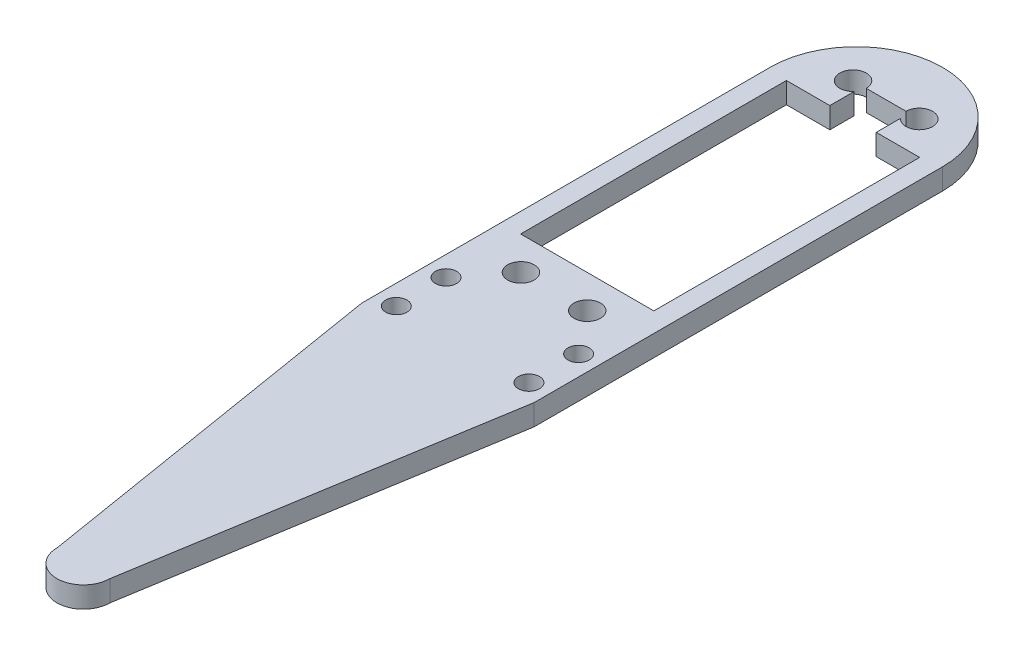
SolidWorks part; units mm, degrees
ref_plane "Front Plane" through (0, 0, 0) normal (0, 0, 1) x (1, 0, 0)
ref_plane "Top Plane" through (0, 0, 0) normal (0, 1, 0) x (1, 0, 0)
ref_plane "Right Plane" through (0, 0, 0) normal (1, 0, 0) x (0, 0, -1)
sketch "Sketch2" plane through (0, 0, 0) normal (0, 1, 0) x (1, 0, 0)
  line L0 (-13, 0) -> (-13, -61.6)
  line L1 (13, 0) -> (13, -61.6)
  line L2 (-13, -61.6) -> (-4, -116.6)
  line L3 (13, -61.6) -> (4, -116.6)
  line L4 (0, 13) -> (0, -120.6) construction
  line L5 (-4, -116.6) -> (4, -116.6) construction
  line L6 (-10.05, -0.5) -> (10.05, -0.5)
  line L7 (-10.05, -0.5) -> (-10.05, -40.6)
  line L8 (-10.05, -40.6) -> (10.05, -40.6)
  line L9 (10.05, -0.5) -> (10.05, -40.6)
  line L10 (-10.05, -0.5) -> (10.05, -40.6) construction
  line L11 (-10.05, -40.6) -> (10.05, -0.5) construction
  arc A0 (13, 0) -> (-13, 0) centre (0, 0) ccw
  arc A1 (-4, -116.6) -> (4, -116.6) centre (0, -116.6) ccw
  circle A2 centre (-5, 4.5) radius 2
  circle A4 centre (-5, -45.6) radius 2
  circle A5 centre (5, -45.6) radius 2
  circle A6 centre (5, 4.5) radius 2
  point P15 (0, -20.55)
  dimension "D1" = 4
  dimension "D8" = 13
  dimension "D10" = 4
  dimension "D2" = 50.1
  dimension "D3" = 5
  dimension "D4" = 4.5
  dimension "D5" = 40.1
  dimension "D6" = 20.1
  dimension "D7" = 5
  dimension "D9" = 55
  dimension "D11" = 16
extrude "Boss-Extrude1" add sketch "Sketch2" along normal blind 3.175
sketch "Sketch3" plane through (0, 3.175, 0) normal (0, 1, 0) x (1, 0, 0)
  circle A0 centre (10, -59.4) radius 1.6 construction
  circle A1 centre (10, -51.9) radius 1.6 construction
  circle A2 centre (-10, -59.4) radius 1.6 construction
  circle A3 centre (-10, -51.9) radius 1.6 construction
  circle A4 centre (10, -59.4) radius 1.6
  circle A5 centre (10, -51.9) radius 1.6
  circle A6 centre (-10, -59.4) radius 1.6
  circle A7 centre (-10, -51.9) radius 1.6
extrude "Cut-Extrude1" cut sketch "Sketch3" against normal through all both and the other way through all
sketch "Sketch4" plane through (0, 3.175, 0) normal (0, 1, 0) x (1, 0, 0)
  line L0 (10.05, -0.5) -> (-10.05, -0.5) construction
  line L1 (-3.5, 4.5) -> (3.5, 4.5)
  line L2 (-3.5, 4.5) -> (-3.5, -0.5)
  line L3 (-3.5, -0.5) -> (3.5, -0.5)
  line L4 (3.5, 4.5) -> (3.5, -0.5)
  line L5 (-3.5, 4.5) -> (3.5, -0.5) construction
  line L6 (-3.5, -0.5) -> (3.5, 4.5) construction
  point P0 (0, 2)
  point P5 (0, -0.5)
  dimension "D1" = 7
  dimension "D2" = 5
extrude "Cut-Extrude2" cut sketch "Sketch4" along direction (0, 1, 0) on the side against the normal up to surface (3.175 mm away)
